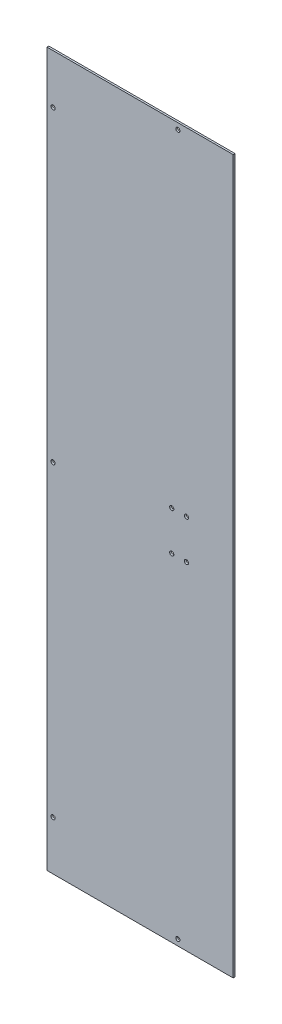
SolidWorks part; units mm, degrees
other "Top Cover Panel 3"
ref_plane "Front Plane" through (0, 0, 0) normal (0, 0, 1) x (1, 0, 0)
ref_plane "Top Plane" through (0, 0, 0) normal (0, 1, 0) x (1, 0, 0)
ref_plane "Right Plane" through (0, 0, 0) normal (1, 0, 0) x (0, 0, -1)
sketch3d "Main Profile Sketch datum points"
  point P0 (0, 0, 111.5)
  point P1 (10, 0, 111.5)
  point P2 (0, 10, 111.5)
ref_plane "Main Profile Sketch plane" through (0, 0, 111.5) normal (0, 0, 1) x (1, 0, 0)
sketch "Main Profile Sketch" plane through (0, 0, 111.5) normal (0, 0, 1) x (1, 0, 0)
  line L0 (83.5, 290) -> (235, 290)
  line L1 (235, 290) -> (235, -290)
  line L2 (83.5, -290) -> (235, -290)
  line L3 (83.5, 290) -> (83.5, -290)
  circle A0 centre (88.5, -250) radius 1.7
  circle A1 centre (190, -285) radius 1.7
  circle A2 centre (185, -16) radius 1.7
  circle A3 centre (197, -16) radius 1.7
  circle A4 centre (88.5, 0) radius 1.7
  circle A5 centre (88.5, 250) radius 1.7
  circle A6 centre (185, 16) radius 1.7
  circle A7 centre (197, 16) radius 1.7
  circle A8 centre (190, 285) radius 1.7
extrude "Main Extrusion" add sketch "Main Profile Sketch" against normal blind 1.5 separate body
